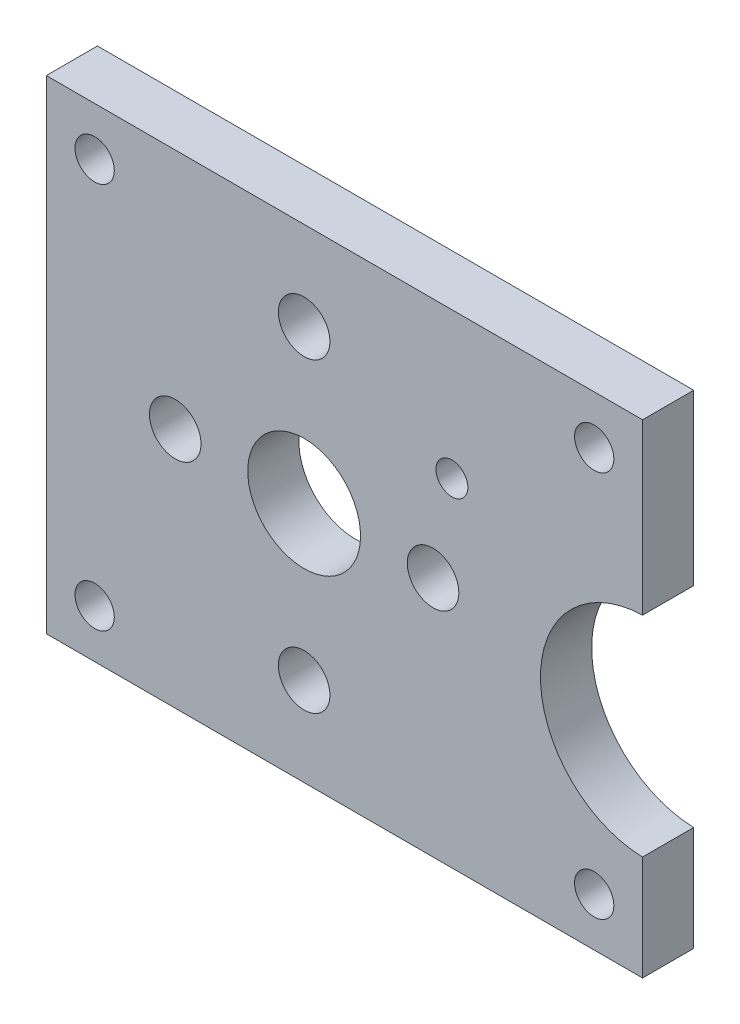
SolidWorks part; units mm, degrees
ref_plane "Front Plane" through (0, 0, 0) normal (0, 0, 1) x (1, 0, 0)
ref_plane "Top Plane" through (0, 0, 0) normal (0, 1, 0) x (1, 0, 0)
ref_plane "Right Plane" through (0, 0, 0) normal (1, 0, 0) x (0, 0, -1)
sketch "Sketch1" plane through (0, 0, 0) normal (0, 0, 1) x (1, 0, 0)
  line L0 (70, 15) -> (0, 15) construction
  line L1 (0, 0) -> (37, 0)
  line L2 (0, 0) -> (0, 30)
  line L3 (0, 30) -> (37, 30)
  line L4 (70, 0) -> (70, 30) construction
  line L5 (16, 24.5) -> (16, 15) construction
  line L6 (37, 30) -> (37, 0) construction
  line L7 (37, 19.4979) -> (37, 30)
  line L8 (37, 6.5021) -> (37, 0)
  line L9 (37, 30) -> (70, 30) construction
  line L10 (37, 0) -> (70, 0) construction
  circle A0 centre (55, 15) radius 2.4892 construction
  circle A1 centre (37.1667, 13) radius 1.4986 construction
  circle A2 centre (25.1698, 20.9334) radius 0.9906
  circle A3 centre (37.1667, 13) radius 11.4777 construction
  circle A4 centre (25.1698, 20.9334) radius 7.1501 construction
  circle A5 centre (55, 15) radius 12.827 construction
  circle A6 centre (16, 15) radius 14 construction
  circle A7 centre (37.1667, 13) radius 5.1181 construction
  circle A8 centre (16, 24.5) radius 1.6
  circle A9 centre (24, 15) radius 1.6
  circle A10 centre (16, 5.5) radius 1.6
  circle A11 centre (8, 15) radius 1.6
  arc A12 (37, 19.4979) -> (37, 6.5021) centre (37.1667, 13) ccw
  circle A13 centre (16, 15) radius 3.5
  point P7 (55, 15)
  point P8 (37.1667, 13)
  point P9 (25.1698, 20.9334)
  point P19 (16, 15)
  dimension "D6" = 4.9784
  dimension "D7" = 2.9972
  dimension "D8" = 1.9812
  dimension "D9" = 25.654
  dimension "D10" = 22.9553
  dimension "D11" = 14.3002
  dimension "D13" = 28
  dimension "D14" = 10.2362
  dimension "D17" = 3.2
  dimension "D18" = 9.5
  dimension "D20" = 6.5
  dimension "D21" = 7
  dimension "D1" = 17.9451
  dimension "D2" = 14.3828
  dimension "D3" = 30
  dimension "D4" = 70
  dimension "D5" = 15
  dimension "D12" = 10.922
  dimension "D15" = 16
  dimension "D16" = 13
  dimension "D19" = 8
  dimension "D22" = 37
extrude "Boss-Extrude2" add sketch "Sketch1" along normal blind 3.175
hole_wizard "#2 Clearance Hole1" positions "Sketch3" profile "Sketch4" hole size "#2" standard "ANSI Inch"
sketch "Sketch3" plane through (0, 0, 3.175) normal (0, 0, 1) x (1, 0, 0)
  line L0 (3, 30) -> (3, 0) construction
  line L1 (37, 30) -> (0, 30) construction
  line L2 (0, 0) -> (37, 0) construction
  line L4 (34, 30) -> (34, 0) construction
  line L6 (0, 30) -> (0, 0) construction
  line L7 (37, 19.4979) -> (37, 30) construction
  point P19 (3, 27)
  point P21 (3, 3)
  point P23 (34, 3)
  point P25 (34, 27)
  dimension "D1" = 3
  dimension "D2" = 3
  dimension "D3" = 3
  dimension "D4" = 3
  dimension "D5" = 3
  dimension "D6" = 3
sketch "Sketch4" plane through (3, 27, 3.175) normal (1, 0, 0) x (0, -1, 0)
  line L0 (0, 0) -> (0, 4.0346)
  line L1 (0, 4.0346) -> (1.2192, 3.302)
  line L2 (1.2192, 3.302) -> (1.2192, 0)
  line L5 (1.2192, 0) -> (0, 0)
  line L10 (0, 4.0346) -> (-1.2192, 3.302) construction
  line L11 (0, -6.35) -> (0, 107.95) construction
  dimension "Hole Dia." = 2.4384
  dimension "Hole Depth" = 3.302
  dimension "Drill Angle" = 118
